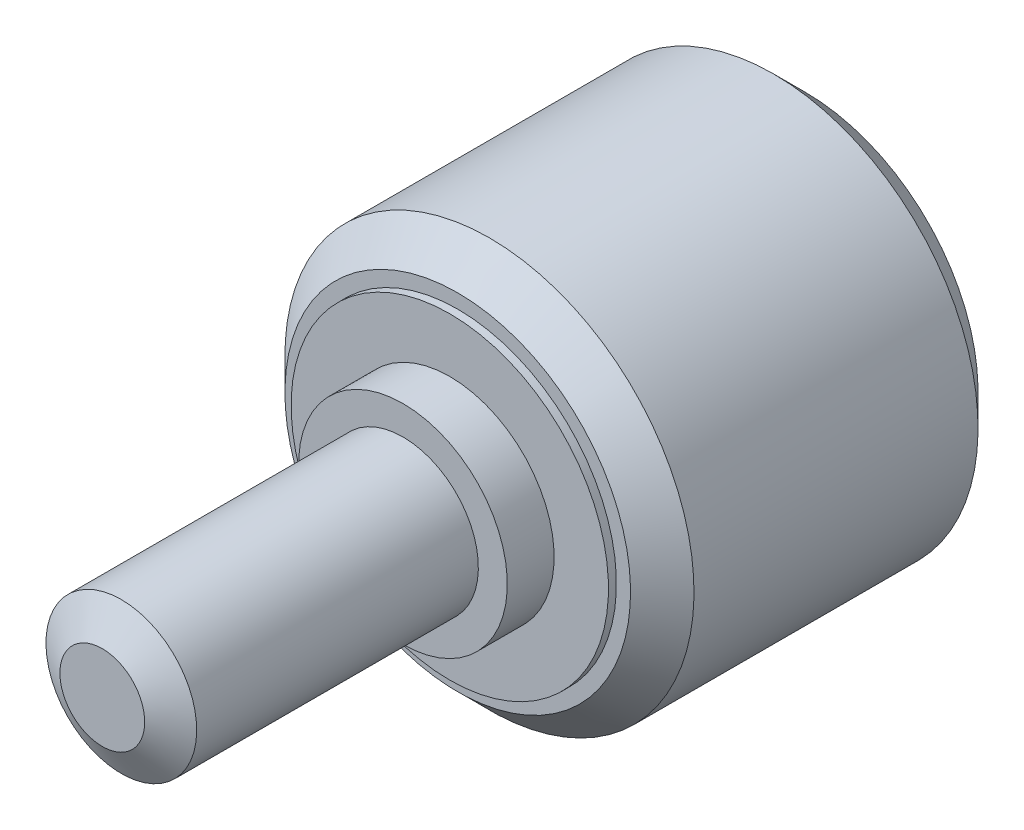
SolidWorks part; units mm, degrees
ref_plane "Front Plane" through (0, 0, 0) normal (0, 0, 1) x (1, 0, 0)
ref_plane "Top Plane" through (0, 0, 0) normal (0, 1, 0) x (1, 0, 0)
ref_plane "Right Plane" through (0, 0, 0) normal (1, 0, 0) x (0, 0, -1)
sketch "Sketch1" plane through (0, 0, 0) normal (1, 0, 0) x (0, 0, -1)
  line L0 (-1.4986, 2.413) -> (-1.4986, 3.3401)
  line L1 (-1.4986, 3.3401) -> (0, 3.3401)
  line L2 (0.254, 5.08) -> (0.254, 5.5324)
  line L3 (1.27, 6.5484) -> (10.3632, 6.5484)
  line L4 (10.3632, 6.5484) -> (11.3792, 5.5324)
  line L5 (11.3792, 5.5324) -> (11.3792, 0)
  line L6 (11.3792, 0) -> (-11.1252, 0)
  line L7 (-11.1252, 0) -> (-11.1252, 1.3571)
  line L8 (-11.1252, 1.3571) -> (-10.5156, 2.413)
  line L9 (-10.5156, 2.413) -> (-1.4986, 2.413)
  line L10 (-11.1252, 0) -> (-78.1415, 0) construction
  line L11 (0.254, 5.08) -> (0, 5.08)
  line L12 (0, 5.08) -> (0, 3.3401)
  line L13 (0.254, 5.5324) -> (1.27, 6.5484)
  dimension "D1" = 4.826
  dimension "D2" = 0.6096
  dimension "D3" = 60
  dimension "D4" = 6.6802
  dimension "D5" = 1.4986
  dimension "D6" = 0.254
  dimension "D7" = 13.0969
  dimension "D8" = 1.016
  dimension "D9" = 45
  dimension "D10" = 11.1252
  dimension "D11" = 11.1252
  dimension "D12" = 10.16
revolve "Revolve1" add sketch "Sketch1" angle 360 about L10
